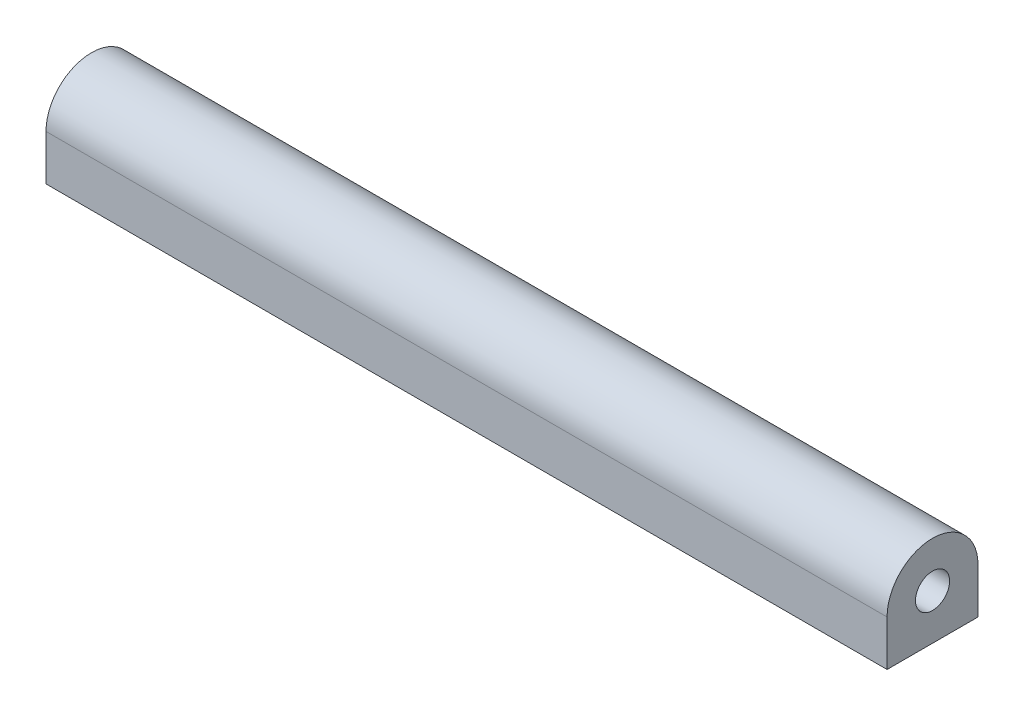
SolidWorks part; units mm, degrees
ref_plane "Front Plane" through (0, 0, 0) normal (0, 0, 1) x (1, 0, 0)
ref_plane "Top Plane" through (0, 0, 0) normal (0, 1, 0) x (1, 0, 0)
ref_plane "Right Plane" through (0, 0, 0) normal (1, 0, 0) x (0, 0, -1)
sketch "Sketch1" plane through (0, 0, 0) normal (1, 0, 0) x (0, 0, -1)
  line L0 (-4, 0) -> (-4, -4)
  line L1 (-4, -4) -> (4, -4)
  line L2 (4, -4) -> (4, 0)
  circle A0 centre (0, 0) radius 1.5
  arc A1 (4, 0) -> (-4, 0) centre (0, 0) ccw
  dimension "D1" = 8
  dimension "D2" = 3
extrude "Boss-Extrude1" add sketch "Sketch1" along normal blind 74
